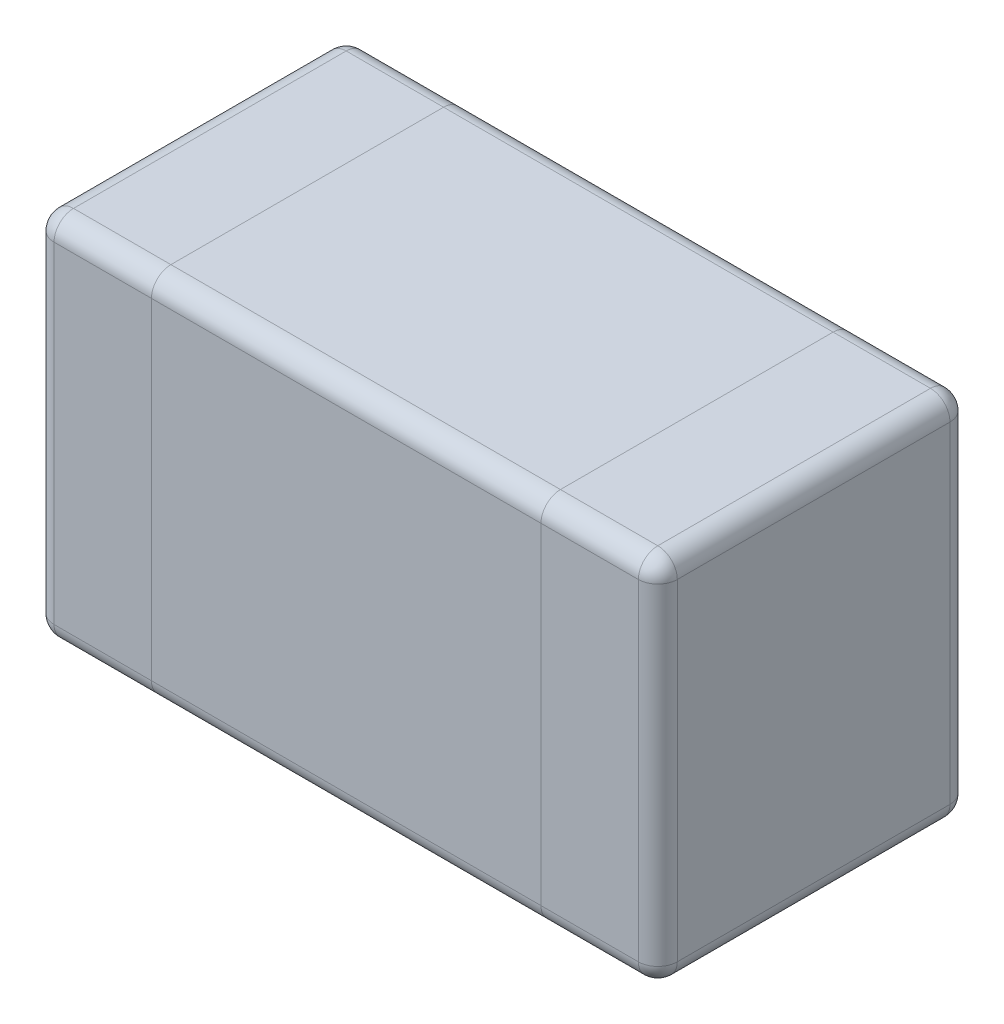
SolidWorks part; units mm, degrees
ref_plane "Front Plane" through (0, 0, 0) normal (0, 0, 1) x (1, 0, 0)
ref_plane "Top Plane" through (0, 0, 0) normal (0, 1, 0) x (1, 0, 0)
ref_plane "Right Plane" through (0, 0, 0) normal (1, 0, 0) x (0, 0, -1)
sketch "Sketch1" plane through (0, 0, 0) normal (0, 1, 0) x (1, 0, 0)
  line L1 (-0.8, -0.4) -> (0.8, -0.4)
  line L2 (-0.8, -0.4) -> (-0.8, 0.4)
  line L3 (-0.8, 0.4) -> (0.8, 0.4)
  line L4 (0.8, -0.4) -> (0.8, 0.4)
  line L5 (-0.8, -0.4) -> (0.8, 0.4) construction
  line L6 (-0.8, 0.4) -> (0.8, -0.4) construction
  point P0 (0, 0)
  dimension "D1" = 1.6
  dimension "D2" = 0.8
extrude "Extrude1" add sketch "Sketch1" along normal blind 0.95
fillet "Fillet1" radius 0.05 12 edges at (0.8, 0.475, -0.4) (-0.8, 0.475, -0.4) (-0.8, 0.475, 0.4) (0.8, 0.475, 0.4) (0, 0.95, 0.4) (-0.8, 0.95, 0) (0, 0.95, -0.4) (0.8, 0.95, 0) (0, 0, -0.4) (-0.8, 0, 0) (0, 0, 0.4) (0.8, 0, 0)
sketch "Sketch2" plane through (0, 0, 0) normal (0, 1, 0) x (1, 0, 0)
  line L0 (-0.75, 0.4) -> (0.75, 0.4) construction
  line L1 (-0.5, -0.4) -> (0.5, -0.4)
  line L2 (-0.5, -0.4) -> (-0.5, 0.4)
  line L3 (-0.5, 0.4) -> (0.5, 0.4)
  line L4 (0.5, -0.4) -> (0.5, 0.4)
  line L5 (0.75, -0.4) -> (-0.75, -0.4) construction
  line L6 (0, 0.35) -> (0, -0.6635) construction
  line L7 (0.75, 0.35) -> (-0.75, 0.35) construction
  line L9 (-0.8, -0.35) -> (-0.8, 0.35) construction
  dimension "D1" = 0.3
split line "Split Line3"
